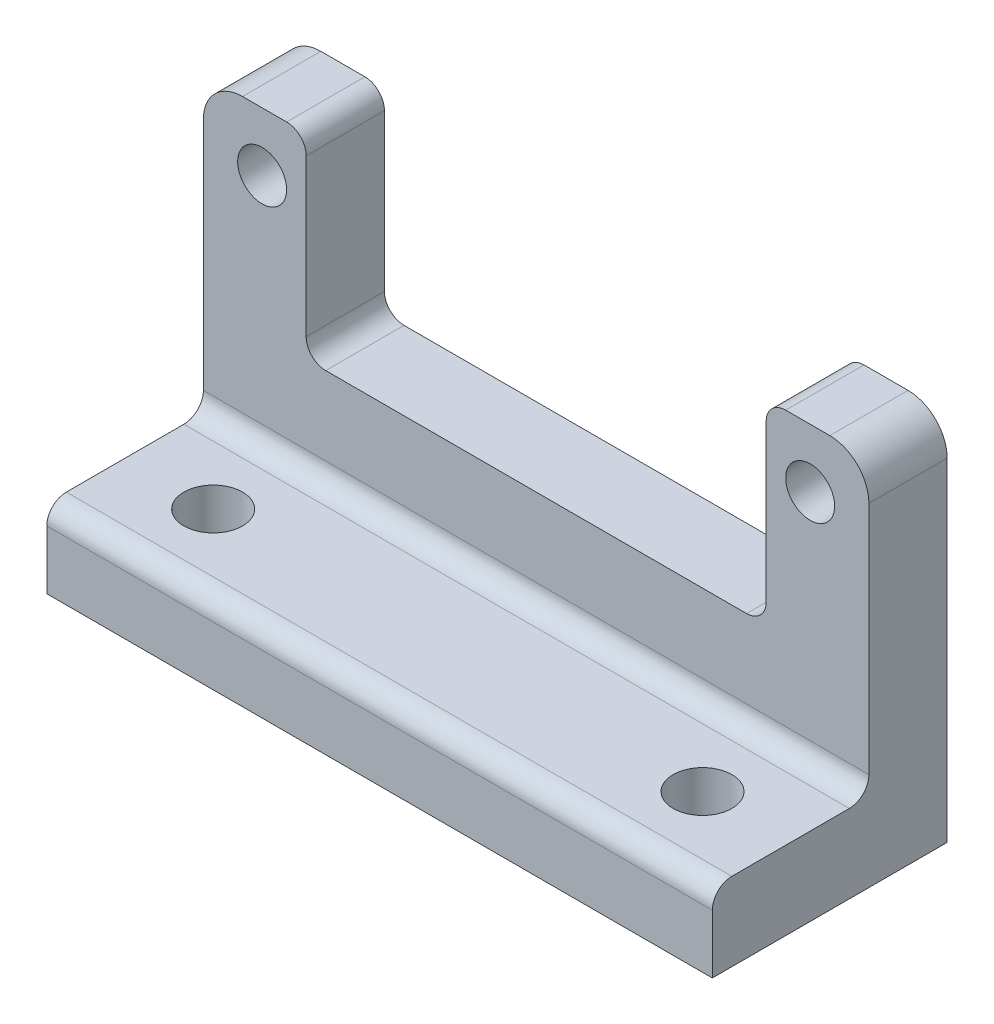
SolidWorks part; units mm, degrees
ref_plane "前视基准面" through (0, 0, 0) normal (0, 0, 1) x (1, 0, 0)
ref_plane "上视基准面" through (0, 0, 0) normal (0, 1, 0) x (1, 0, 0)
ref_plane "右视基准面" through (0, 0, 0) normal (1, 0, 0) x (0, 0, -1)
sketch "草图1" plane through (0, 0, 0) normal (0, 1, 0) x (1, 0, 0)
  line L0 (4.5, -8) -> (29.5, -8) construction
  line L1 (0, 0) -> (34, 0)
  line L2 (0, 0) -> (0, -12)
  line L3 (0, -12) -> (34, -12)
  line L4 (34, 0) -> (34, -12)
  line L5 (17, -12) -> (17, -8) construction
  circle A0 centre (4.5, -8) radius 1.5
  circle A1 centre (29.5, -8) radius 1.5
  dimension "D2" = 3
  dimension "D1" = 12
  dimension "D3" = 34
  dimension "D4" = 25
  dimension "D5" = 4
extrude "凸台-拉伸4" add sketch "草图1" along normal blind 4
sketch "草图4" plane through (0, 4, 0) normal (0, 1, 0) x (1, 0, 0)
  line L0 (34, -12) -> (34, 0) construction
  line L1 (0, 0) -> (34, 0)
  line L2 (0, 0) -> (0, -4)
  line L3 (0, -4) -> (34, -4)
  line L4 (34, 0) -> (34, -4)
  dimension "D1" = 4
extrude "凸台-拉伸5" add sketch "草图4" along normal blind 15
sketch "草图5" plane through (0, 0, 4) normal (0, 0, 1) x (1, 0, 0)
  line L0 (3, 16) -> (31, 16) construction
  line L1 (17, 16) -> (17, 4) construction
  line L2 (0, 4) -> (34, 4) construction
  line L4 (0, 0) -> (34, 0) construction
  line L5 (0, 19) -> (34, 19) construction
  line L6 (5.25, 19) -> (28.75, 19)
  line L7 (5.25, 19) -> (5.25, 9)
  line L8 (5.25, 9) -> (28.75, 9)
  line L9 (28.75, 19) -> (28.75, 9)
  circle A0 centre (3, 16) radius 1.25
  circle A1 centre (31, 16) radius 1.25
  point P16 (17, 9)
  dimension "D1" = 2.5
  dimension "D2" = 28
  dimension "D3" = 16
  dimension "D4" = 7
  dimension "D5" = 23.5
extrude "切除-拉伸1" cut sketch "草图5" against normal through all contours L7 L6 L9 L8 | A1 | A0
fillet "圆角4" radius 1 1 edges at (17, 4, 12)
fillet "圆角6" radius 2 1 edges at (0, 19, 2)
fillet "圆角7" radius 2 1 edges at (34, 19, 2)
fillet "圆角8" radius 1 1 edges at (5.25, 9, 2)
fillet "圆角9" radius 1 1 edges at (28.75, 9, 2)
fillet "圆角10" radius 1 2 edges at (5.25, 19, 2) (28.75, 19, 2)
fillet "圆角11" radius 1 1 edges at (17, 4, 4)
